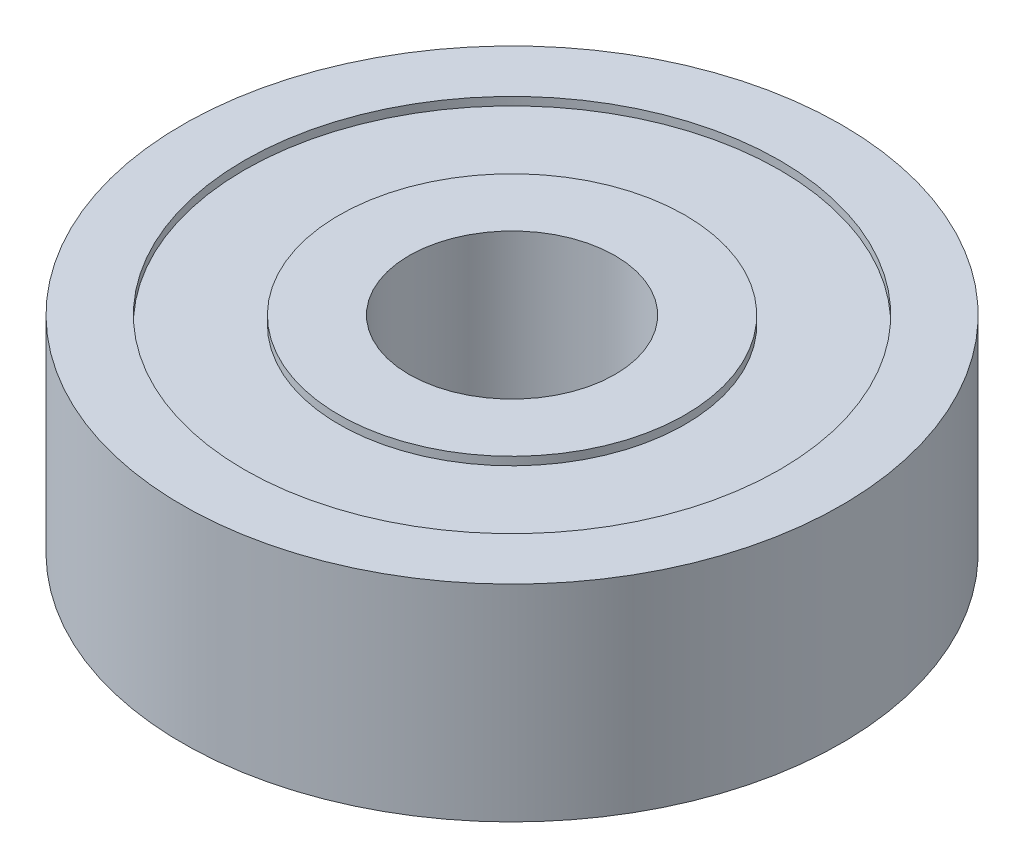
SolidWorks part; units mm, degrees
ref_plane "Alzado" through (0, 0, 0) normal (0, 0, 1) x (1, 0, 0)
ref_plane "Planta" through (0, 0, 0) normal (0, 1, 0) x (1, 0, 0)
ref_plane "Vista lateral" through (0, 0, 0) normal (1, 0, 0) x (0, 0, -1)
sketch "Croquis1" plane through (0, 0, 0) normal (0, 0, 1) x (1, 0, 0)
  line L0 (0, -2.5) -> (0, 2.5) construction
  line L1 (0, 0) -> (2.5, 0) construction
  line L2 (2.5, -2.5) -> (2.5, 2.5)
  line L3 (2.5, 2.5) -> (4.2, 2.5)
  line L4 (4.2, 2.5) -> (4.2, 2.3)
  line L5 (4.2, 2.3) -> (6.5, 2.3)
  line L6 (6.5, 2.3) -> (6.5, 2.5)
  line L7 (6.5, 2.5) -> (8, 2.5)
  line L8 (6.5, -2.5) -> (8, -2.5)
  line L9 (6.5, -2.3) -> (6.5, -2.5)
  line L10 (4.2, -2.5) -> (4.2, -2.3)
  line L11 (4.2, -2.3) -> (6.5, -2.3)
  line L12 (2.5, -2.5) -> (4.2, -2.5)
  line L13 (8, 2.5) -> (8, -2.5)
  dimension "D1" = 5
  dimension "D2" = 2.5
  dimension "D3" = 4.2
  dimension "D4" = 6.5
  dimension "D5" = 8
  dimension "D6" = 0.2
  dimension "D7" = 5
  dimension "D8" = 5
revolve "Revolución1" add sketch "Croquis1" angle 360 about L0
